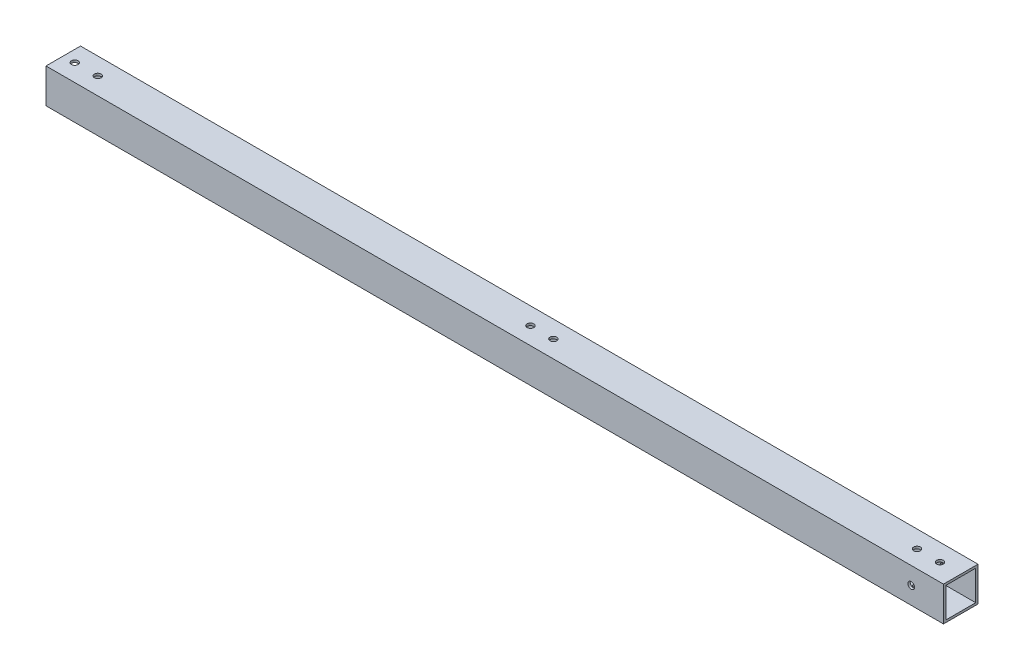
SolidWorks part; units mm, degrees
material "Thornel Mat VMA"
ref_plane "前视基准面" through (0, 0, 0) normal (0, 0, 1) x (1, 0, 0)
ref_plane "上视基准面" through (0, 0, 0) normal (0, 1, 0) x (1, 0, 0)
ref_plane "右视基准面" through (0, 0, 0) normal (1, 0, 0) x (0, 0, -1)
other "Configuration Table"
sketch "草图1" plane through (0, 0, 0) normal (1, 0, 0) x (0, 0, -1)
  line L0 (-6.5, -6.5) -> (-6.5, 6.5)
  line L1 (-7.5, -7.5) -> (7.5, -7.5)
  line L2 (-7.5, -7.5) -> (-7.5, 7.5)
  line L3 (-7.5, 7.5) -> (7.5, 7.5)
  line L4 (7.5, -7.5) -> (7.5, 7.5)
  line L5 (-7.5, -7.5) -> (7.5, 7.5) construction
  line L6 (-7.5, 7.5) -> (7.5, -7.5) construction
  line L7 (-6.5, 6.5) -> (6.5, 6.5)
  line L8 (6.5, -6.5) -> (6.5, 6.5)
  line L9 (-6.5, -6.5) -> (6.5, -6.5)
  point P0 (0, 0)
  dimension "D1" = 15
  dimension "D2" = 15
  dimension "D3" = 1
extrude "凸台-拉伸1" add sketch "草图1" along normal blind 390
sketch "草图2" plane through (0, 7.5, 0) normal (0, 1, 0) x (1, 0, 0)
  line L0 (-10.5855, 0) -> (412.192, 0) construction
  line L2 (390, 7.5) -> (390, -7.5) construction
  circle A2 centre (203, 0) radius 1.45
  circle A3 centre (213, 0) radius 1.45
  circle A4 centre (15, 0) radius 1.45 construction
  circle A5 centre (5, 0) radius 1.45 construction
  circle A6 centre (381, 0) radius 1.45 construction
  circle A7 centre (371, 0) radius 1.45 construction
  circle A8 centre (15, 0) radius 1.45
  circle A9 centre (5, 0) radius 1.45
  circle A10 centre (381, 0) radius 1.45
  circle A11 centre (371, 0) radius 1.45
  dimension "D2" = 187
  dimension "D3" = 2.9
  dimension "D1" = 177
  dimension "D4" = 2.9
extrude "切除-拉伸1" cut sketch "草图2" against normal through all
sketch "草图3" plane through (0, 0, -7.5) normal (0, 0, -1) x (-1, 0, 0)
  circle A0 centre (-376, 0) radius 1.45 construction
  circle A1 centre (-376, 0) radius 1.45
extrude "切除-拉伸2" cut sketch "草图3" against normal through all
